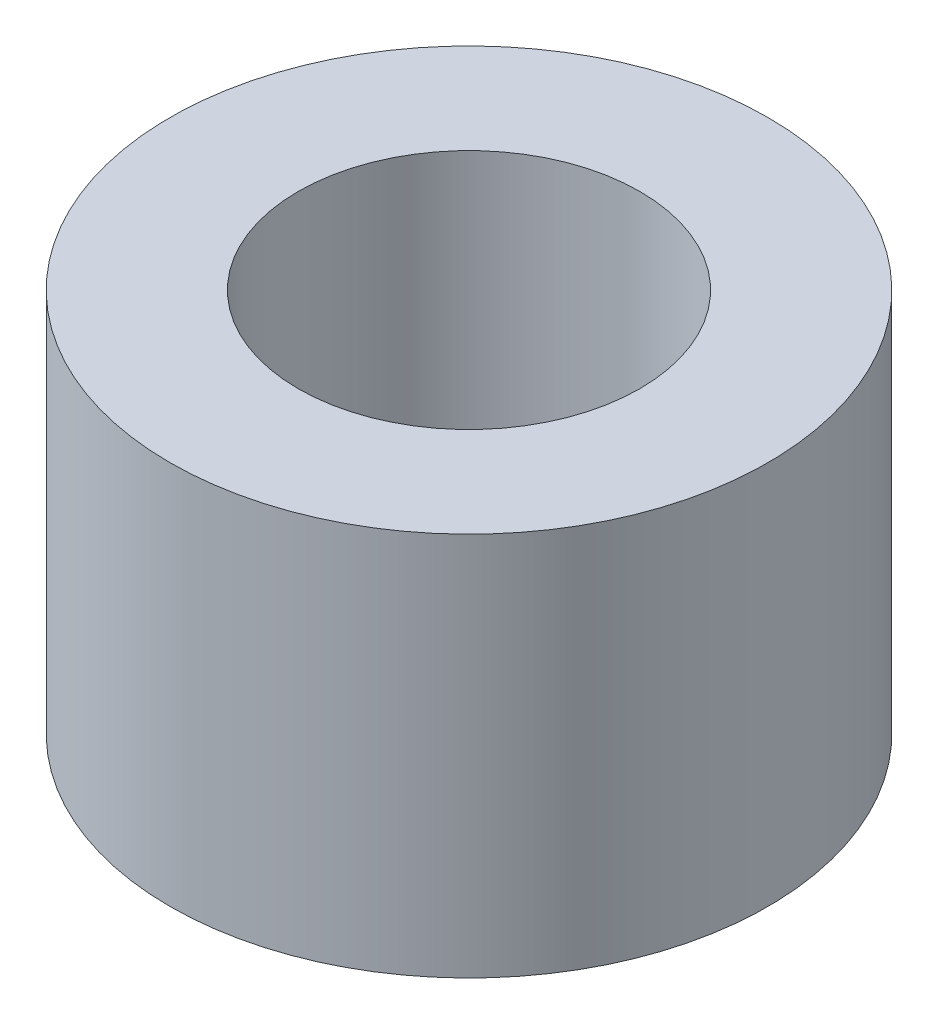
SolidWorks part; units mm, degrees
ref_plane "Alzado" through (0, 0, 0) normal (0, 0, 1) x (1, 0, 0)
ref_plane "Planta" through (0, 0, 0) normal (0, 1, 0) x (1, 0, 0)
ref_plane "Vista lateral" through (0, 0, 0) normal (1, 0, 0) x (0, 0, -1)
sketch "Croquis1" plane through (0, 0, 0) normal (0, 1, 0) x (1, 0, 0)
  circle A0 centre (0, 0) radius 7
  circle A1 centre (0, 0) radius 4
  dimension "D1" = 14
  dimension "D2" = 8
extrude "Saliente-Extruir1" add sketch "Croquis1" along normal blind 9
